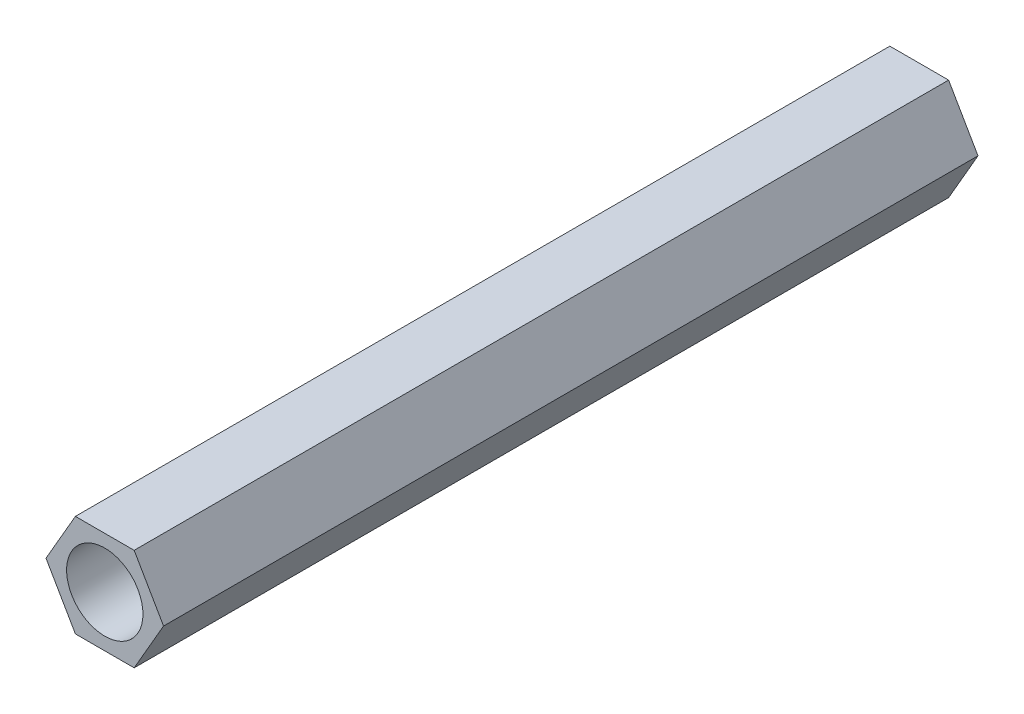
SolidWorks part; units mm, degrees
ref_plane "前视基准面" through (0, 0, 0) normal (0, 0, 1) x (1, 0, 0)
ref_plane "上视基准面" through (0, 0, 0) normal (0, 1, 0) x (1, 0, 0)
ref_plane "右视基准面" through (0, 0, 0) normal (1, 0, 0) x (0, 0, -1)
other "Configuration Table"
sketch "草图1" plane through (0, 0, 0) normal (0, 0, 1) x (1, 0, 0)
  line L1 (2.3094, 0) -> (1.1547, 2)
  line L2 (1.1547, 2) -> (-1.1547, 2)
  line L3 (-1.1547, 2) -> (-2.3094, 0)
  line L4 (-2.3094, 0) -> (-1.1547, -2)
  line L5 (-1.1547, -2) -> (1.1547, -2)
  line L6 (1.1547, -2) -> (2.3094, 0)
  circle A0 centre (0, 0) radius 2 construction
  circle A1 centre (0, 0) radius 1.5
  dimension "D1" = 2
extrude "凸台-拉伸1" add sketch "草图1" along normal blind 32
